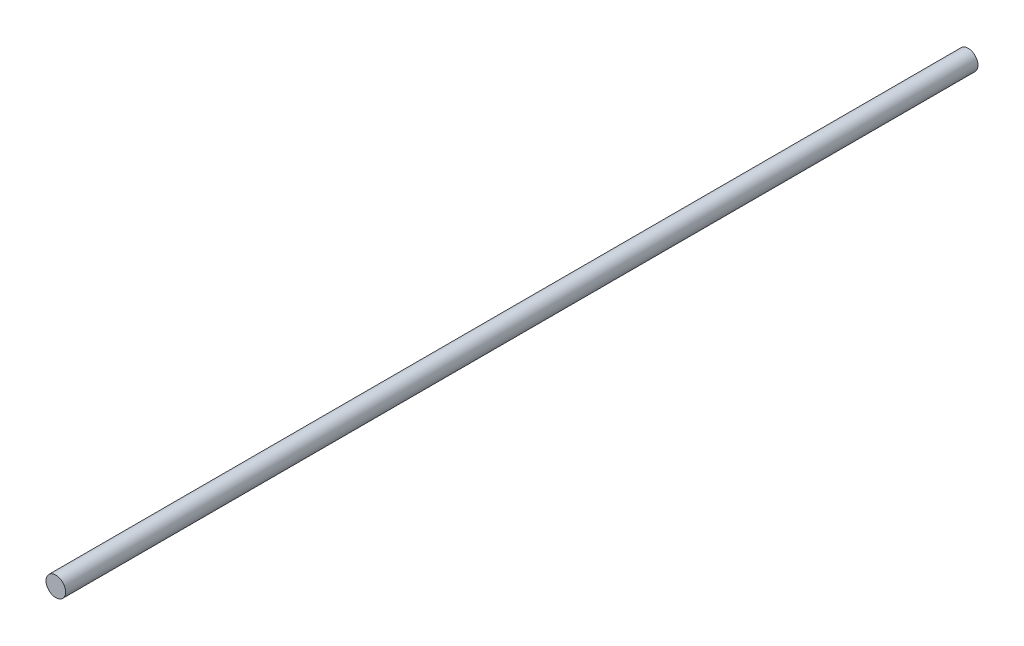
SolidWorks part; units mm, degrees
material "6061 Alloy"
ref_plane "Front Plane" through (0, 0, 0) normal (0, 0, 1) x (1, 0, 0)
ref_plane "Top Plane" through (0, 0, 0) normal (0, 1, 0) x (1, 0, 0)
ref_plane "Right Plane" through (0, 0, 0) normal (1, 0, 0) x (0, 0, -1)
sketch "Sketch1" plane through (0, 0, 0) normal (0, 0, 1) x (1, 0, 0)
  circle A0 centre (0, 0) radius 6.35
  dimension "D1" = 12.7
extrude "Boss-Extrude1" add sketch "Sketch1" along normal blind 590.3
